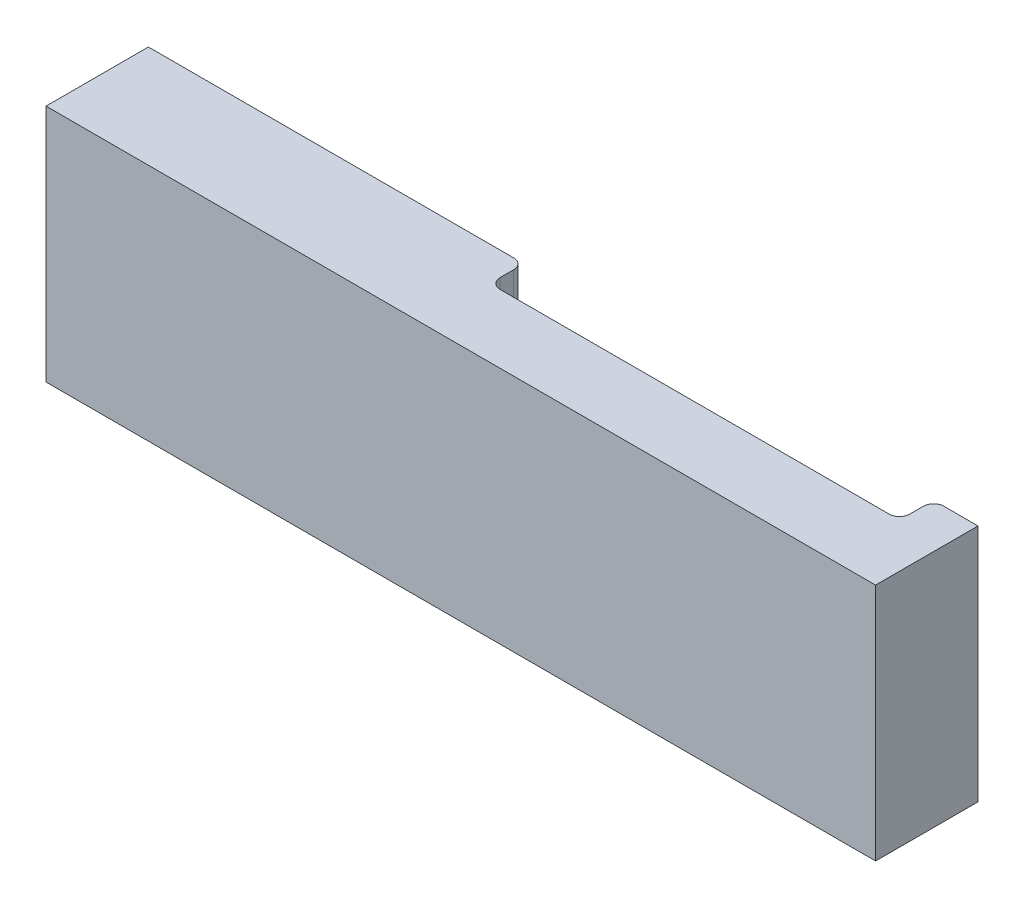
SolidWorks part; units mm, degrees
ref_plane "Front Plane" through (0, 0, 0) normal (0, 0, 1) x (1, 0, 0)
ref_plane "Top Plane" through (0, 0, 0) normal (0, 1, 0) x (1, 0, 0)
ref_plane "Right Plane" through (0, 0, 0) normal (1, 0, 0) x (0, 0, -1)
sketch "Sketch1" plane through (0, 0, 0) normal (0, 1, 0) x (1, 0, 0)
  line L1 (-215.929, 7.0632) -> (27.071, 7.0632)
  line L2 (-215.929, 7.0632) -> (-215.929, -22.9368)
  line L3 (-215.929, -22.9368) -> (27.071, -22.9368)
  line L4 (27.071, 7.0632) -> (27.071, -22.9368)
  dimension "D1" = 30
  dimension "D2" = 243
extrude "Boss-Extrude1" add sketch "Sketch1" along normal blind 70
sketch "Sketch2" plane through (0, 70, 0) normal (0, 1, 0) x (1, 0, 0)
  line L0 (27.071, -22.9368) -> (27.071, 7.0632) construction
  line L1 (14.071, -2.9368) -> (-105.929, -2.9368)
  line L2 (14.071, -2.9368) -> (14.071, 7.0632)
  line L3 (14.071, 7.0632) -> (-105.929, 7.0632)
  line L4 (-105.929, -2.9368) -> (-105.929, 7.0632)
  line L5 (27.071, 7.0632) -> (-215.929, 7.0632) construction
  dimension "D1" = 13
  dimension "D2" = 0
  dimension "D3" = 120
  dimension "D4" = 10
extrude "Cut-Extrude1" cut sketch "Sketch2" against normal blind 70
fillet "Fillet1" radius 3 4 edges at (14.071, 35, -7.0632) (14.071, 35, 2.9368) (-105.929, 35, -7.0632) (-105.929, 35, 2.9368)
sketch "Sketch3" plane through (0, 0, 0) normal (0, -1, 0) x (-1, 0, 0)
  line L0 (215.929, -22.9368) -> (-27.071, -22.9368) construction
  line L2 (215.929, 7.0632) -> (215.929, -22.9368) construction
  circle A0 centre (51.299, -12.0779) radius 3
  circle A1 centre (185.929, -2.9368) radius 3
  dimension "D1" = 20
  dimension "D2" = 10.859
  dimension "D3" = 30
  dimension "D4" = 134.63
extrude "Cut-Extrude2" cut sketch "Sketch3" against normal blind 20
sketch "Sketch4" plane through (0, 0, 0) normal (0, -1, 0) x (-1, 0, 0)
  circle A0 centre (188.5755, -9.3514) radius 11.0002
  circle A2 centre (51.299, -12.0779) radius 5.9074
extrude "Boss-Extrude2" add sketch "Sketch4" against normal blind 39
sketch "Sketch5" plane through (0, 0, 0) normal (0, -1, 0) x (-1, 0, 0)
  line L0 (215.929, 7.0632) -> (215.929, -22.9368) construction
  line L1 (215.929, -22.9368) -> (-27.071, -22.9368) construction
  circle A0 centre (51.299, -12.9368) radius 1.5
  circle A1 centre (185.929, -2.9368) radius 1.5
  dimension "D1" = 30
  dimension "D2" = 20
  dimension "D3" = 134.63
  dimension "D4" = 10
extrude "Cut-Extrude3" cut sketch "Sketch5" against normal blind 20
